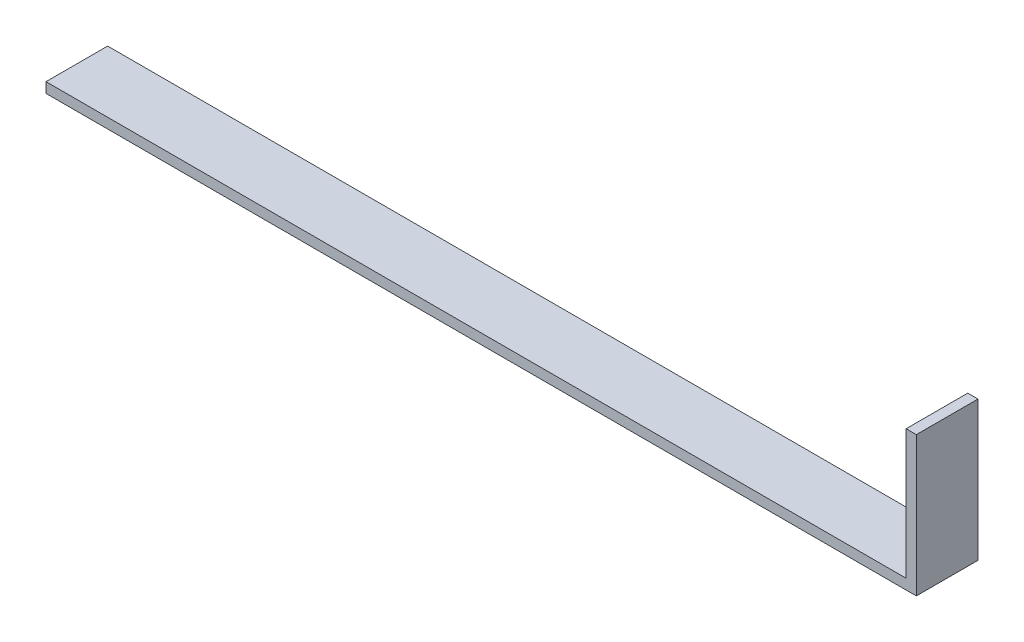
SolidWorks part; units mm, degrees
ref_plane "Alzado" through (0, 0, 0) normal (0, 0, 1) x (1, 0, 0)
ref_plane "Planta" through (0, 0, 0) normal (0, 1, 0) x (1, 0, 0)
ref_plane "Vista lateral" through (0, 0, 0) normal (1, 0, 0) x (0, 0, -1)
sketch "Croquis1" plane through (0, 0, 0) normal (0, 0, 1) x (1, 0, 0)
  line L0 (0, 0) -> (202.9376, 0)
  line L1 (202.9376, 0) -> (202.9376, 80)
  line L2 (202.9376, 80) -> (349.64, 80)
  line L3 (0, -6.31) -> (209.2476, -6.31)
  line L4 (209.2476, -6.31) -> (209.2476, 73.69)
  line L5 (209.2476, 73.69) -> (349.64, 73.69)
  line L6 (0, 0) -> (0, -6.31)
  line L7 (349.64, 80) -> (349.64, 73.69)
  dimension "D1" = 349.64
  dimension "D2" = 80
  dimension "D3" = 6.31
extrude "Saliente-Extruir1" add sketch "Croquis1" along normal blind 38.1
sketch "Croquis4" plane through (0, 73.69, 0) normal (0, -1, 0) x (1, 0, 0)
  line L0 (209.2476, 0) -> (209.2476, 38.1)
  line L1 (209.2476, 38.1) -> (349.64, 38.1)
  line L2 (349.64, 38.1) -> (349.64, 0)
  line L3 (349.64, 0) -> (209.2476, 0)
extrude "Cortar-Extruir2" cut sketch "Croquis4" against normal blind 6.31
sketch "Croquis5" plane through (0, 0, 0) normal (-1, 0, 0) x (0, 0, 1)
  line L0 (0, 0) -> (38.1, 0)
  line L1 (38.1, 0) -> (38.1, -6.31)
  line L2 (38.1, -6.31) -> (0, -6.31)
  line L3 (0, -6.31) -> (0, 0)
extrude "Saliente-Extruir2" add sketch "Croquis5" along normal blind 328.45
sketch "Croquis7" plane through (202.9376, 0, 0) normal (-1, 0, 0) x (0, 0, 1)
  line L0 (38.1, 80) -> (38.1, 94.8116)
  line L1 (38.1, 80) -> (38.1, 0) construction
  line L2 (38.1, 94.8116) -> (88.1, 94.8116)
  line L3 (88.1, 94.8116) -> (88.1, 80)
  line L4 (88.1, 80) -> (38.1, 80)
  dimension "D1" = 50
